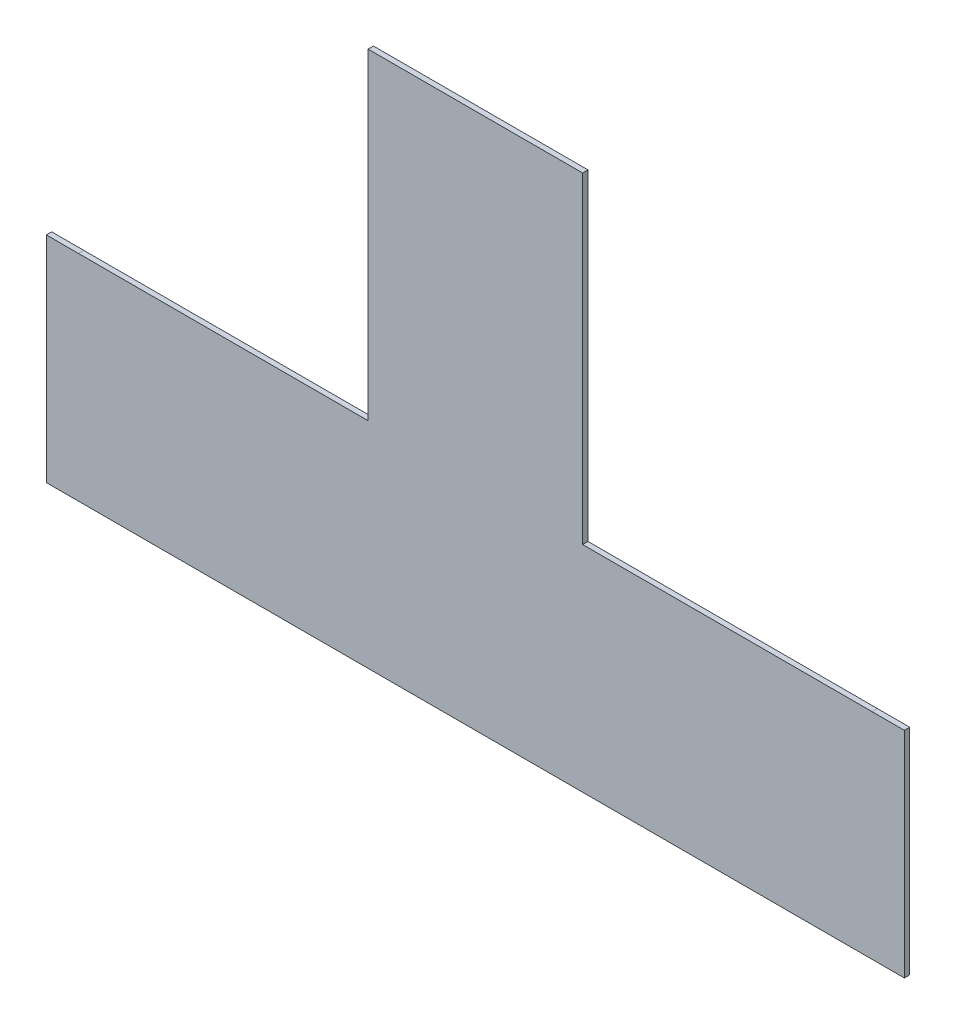
SolidWorks part; units mm, degrees
ref_plane "Front Plane" through (0, 0, 0) normal (0, 0, 1) x (1, 0, 0)
ref_plane "Top Plane" through (0, 0, 0) normal (0, 1, 0) x (1, 0, 0)
ref_plane "Right Plane" through (0, 0, 0) normal (1, 0, 0) x (0, 0, -1)
sketch "Sketch1" plane through (0, 0, 0) normal (0, 0, 1) x (1, 0, 0)
  line L0 (80, 100) -> (80, 0)
  line L1 (0, 0) -> (160, 0)
  line L2 (0, 0) -> (0, 40)
  line L3 (0, 40) -> (60, 40)
  line L6 (60, 40) -> (60, 100)
  line L7 (60, 100) -> (100, 100)
  line L9 (100, 40) -> (100, 100)
  line L10 (160, 40) -> (100, 40)
  line L11 (160, 0) -> (160, 40)
  dimension "D1" = 40
  dimension "D2" = 60
  dimension "D3" = 100
  dimension "D4" = 160
extrude "Boss-Extrude1" add sketch "Sketch1" along normal blind 1 contours L7 L6 L3 L2 L1 L0 | L1 L11 L10 L9 L7 L0
ref_plane "Plane1" through (0, 40, 0) normal (0, 1, 0) x (1, 0, 0)
sketch "Sketch2" plane through (0, 40, 0) normal (0, 1, 0) x (1, 0, 0)
  line L0 (160, 0) -> (100, 0) construction
  line L1 (154, 0) -> (160, 0)
  line L2 (154, 0) -> (154, -1)
  line L3 (154, -1) -> (160, -1)
  line L4 (160, 0) -> (160, -1)
  line L5 (160, -1) -> (160, 0) construction
  line L6 (160, -1) -> (100, -1) construction
  line L7 (0, -1) -> (60, -1) construction
  line L8 (0, 0) -> (6, 0)
  line L9 (0, 0) -> (0, -1)
  line L10 (0, -1) -> (6, -1)
  line L11 (6, 0) -> (6, -1)
  dimension "D1" = 6
  dimension "D2" = 6
split line "Split Line1"
